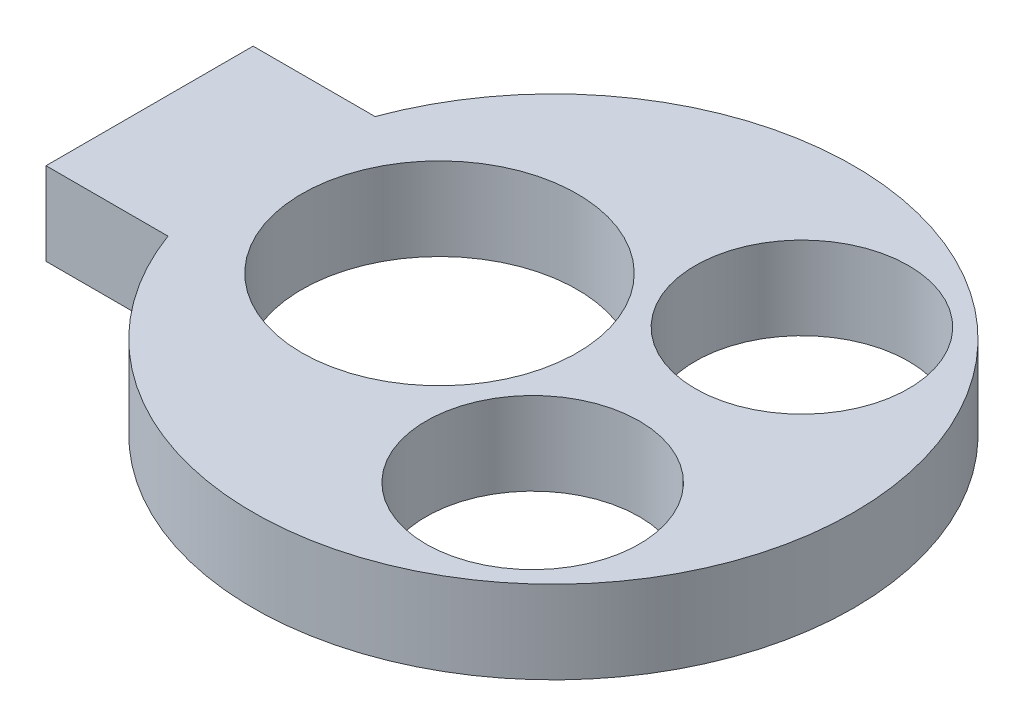
SolidWorks part; units mm, degrees
material "6061 Alloy"
ref_plane "Alzado" through (0, 0, 0) normal (0, 0, 1) x (1, 0, 0)
ref_plane "Planta" through (0, 0, 0) normal (0, 1, 0) x (1, 0, 0)
ref_plane "Vista lateral" through (0, 0, 0) normal (1, 0, 0) x (0, 0, -1)
ref_plane "Plane2" through (0, -2, 0) normal (0, 1, 0) x (1, 0, 0)
sketch "Sketch1" plane through (0, -2, 0) normal (0, 1, 0) x (1, 0, 0)
  circle A0 centre (0, 0) radius 14.5
  circle A1 centre (-5.5, 0) radius 6.65
  circle A2 centre (5.5, -6.5) radius 5.15
  circle A3 centre (5.5, 6.5) radius 5.15
extrude "Disco_separador" add sketch "Sketch1" along normal blind 4
sketch "Sketch2" plane through (0, -2, 0) normal (0, 1, 0) x (1, 0, 0)
  line L0 (-19.5, -5) -> (-12.5, -5)
  line L1 (-12.5, -5) -> (-12.5, 5)
  line L2 (-12.5, 5) -> (-19.5, 5)
  line L3 (-19.5, 5) -> (-19.5, -5)
extrude "Pata_al_hueso" add sketch "Sketch2" along normal blind 4
